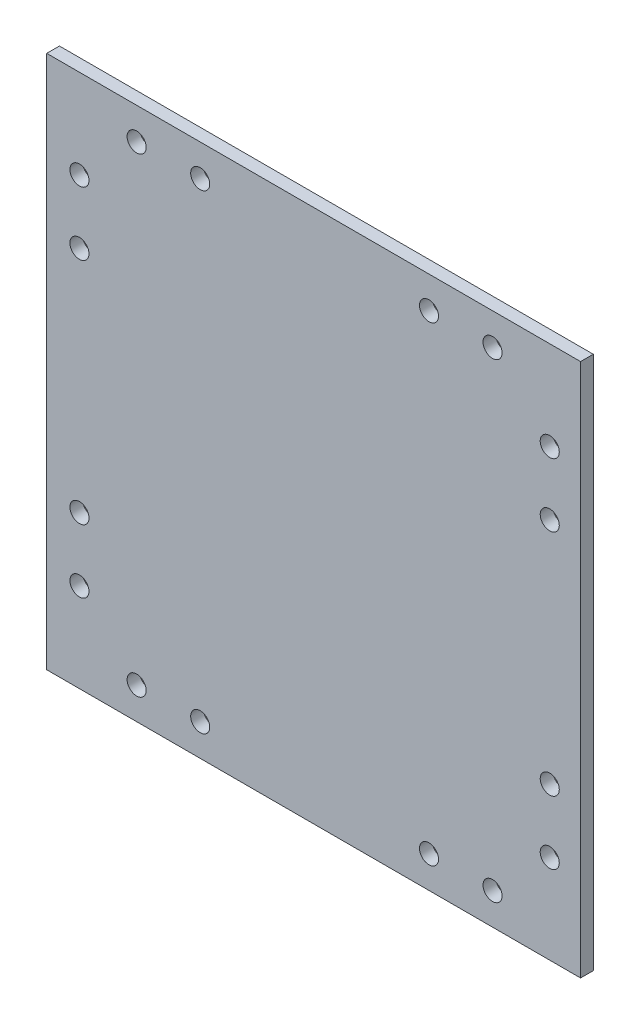
SolidWorks part; units mm, degrees
material "Thornel Mat VMA"
ref_plane "前视基准面" through (0, 0, 0) normal (0, 0, 1) x (1, 0, 0)
ref_plane "上视基准面" through (0, 0, 0) normal (0, 1, 0) x (1, 0, 0)
ref_plane "右视基准面" through (0, 0, 0) normal (1, 0, 0) x (0, 0, -1)
other "Configuration Table"
sketch "草图1" plane through (0, 0, 0) normal (0, 0, 1) x (1, 0, 0)
  line L1 (-42, 42) -> (42, 42)
  line L2 (-42, 42) -> (-42, -42)
  line L3 (-42, -42) -> (42, -42)
  line L4 (42, 42) -> (42, -42)
  line L5 (-42, 42) -> (42, -42) construction
  line L6 (-42, -42) -> (42, 42) construction
  point P0 (0, 0)
  dimension "D1" = 84
  dimension "D2" = 84
extrude "凸台-拉伸1" add sketch "草图1" along normal blind 2
sketch "草图2" plane through (0, 0, 2) normal (0, 0, 1) x (1, 0, 0)
  circle A0 centre (18.15, -37) radius 1.5 construction
  circle A1 centre (28.15, -37) radius 1.5 construction
  circle A2 centre (37.15, -28) radius 1.5 construction
  circle A3 centre (37.15, -18) radius 1.5 construction
  circle A4 centre (37.15, 18) radius 1.5 construction
  circle A5 centre (37.15, 28) radius 1.5 construction
  circle A6 centre (-17.85, -37) radius 1.5 construction
  circle A7 centre (-27.85, -37) radius 1.5 construction
  circle A8 centre (-36.85, -28) radius 1.5 construction
  circle A9 centre (-36.85, -18) radius 1.5 construction
  circle A10 centre (-36.85, 18) radius 1.5 construction
  circle A11 centre (-36.85, 28) radius 1.5 construction
  circle A12 centre (28.15, 37) radius 1.5 construction
  circle A13 centre (18.15, 37) radius 1.5 construction
  circle A14 centre (-17.85, 37) radius 1.5 construction
  circle A15 centre (-27.85, 37) radius 1.5 construction
  circle A16 centre (18.15, -37) radius 1.5
  circle A17 centre (28.15, -37) radius 1.5
  circle A18 centre (37.15, -28) radius 1.5
  circle A19 centre (37.15, -18) radius 1.5
  circle A20 centre (37.15, 18) radius 1.5
  circle A21 centre (37.15, 28) radius 1.5
  circle A22 centre (-17.85, -37) radius 1.5
  circle A23 centre (-27.85, -37) radius 1.5
  circle A24 centre (-36.85, -28) radius 1.5
  circle A25 centre (-36.85, -18) radius 1.5
  circle A26 centre (-36.85, 18) radius 1.5
  circle A27 centre (-36.85, 28) radius 1.5
  circle A28 centre (28.15, 37) radius 1.5
  circle A29 centre (18.15, 37) radius 1.5
  circle A30 centre (-17.85, 37) radius 1.5
  circle A31 centre (-27.85, 37) radius 1.5
extrude "切除-拉伸1" cut sketch "草图2" against normal through all
